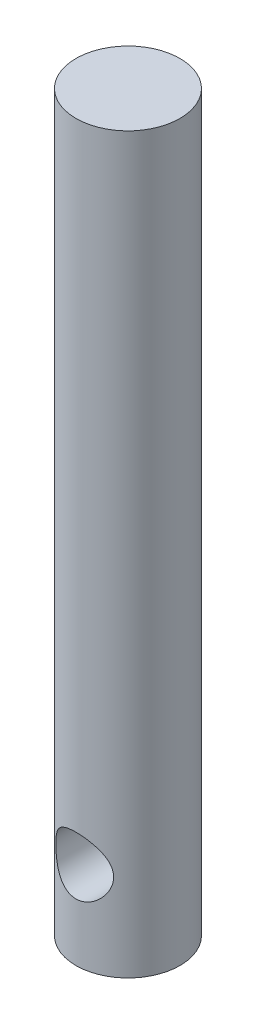
SolidWorks part; units mm, degrees
ref_plane "Front Plane" through (0, 0, 0) normal (0, 0, 1) x (1, 0, 0)
ref_plane "Top Plane" through (0, 0, 0) normal (0, 1, 0) x (1, 0, 0)
ref_plane "Right Plane" through (0, 0, 0) normal (1, 0, 0) x (0, 0, -1)
sketch "Sketch5" plane through (0, 0, 0) normal (0, 1, 0) x (1, 0, 0)
  circle A0 centre (32.6665, 0) radius 9
  point P2 (41.6665, 0)
extrude "Boss-Extrude2" add sketch "Sketch5" along normal blind 127 separate body
ref_plane "Plane1" through (0, 0, 9) normal (0, 0, 1) x (1, 0, 0)
sketch "Sketch7" plane through (0, 0, 9) normal (0, 0, 1) x (1, 0, 0)
  line L0 (41.6665, 0) -> (23.6665, 0)
  line L1 (55, 0) -> (-55, 0) construction
  line L2 (41.6665, 0) -> (41.6665, 127) construction
  line L3 (23.6665, 127) -> (23.6665, 0) construction
  line L4 (32.6665, 0) -> (32.6665, 15) construction
  circle A0 centre (32.6665, 15) radius 5
extrude "Cut-Extrude2" cut sketch "Sketch7" against normal blind 50
